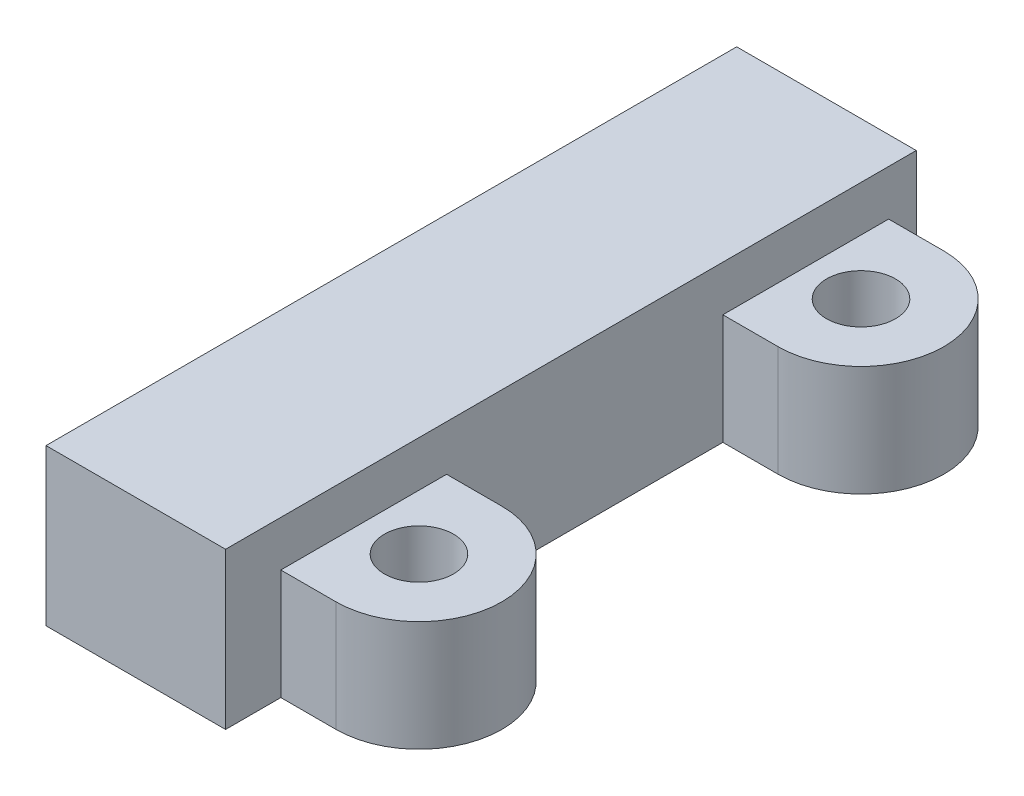
SolidWorks part; units mm, degrees
ref_plane "Alzado" through (0, 0, 0) normal (0, 0, 1) x (1, 0, 0)
ref_plane "Planta" through (0, 0, 0) normal (0, 1, 0) x (1, 0, 0)
ref_plane "Vista lateral" through (0, 0, 0) normal (1, 0, 0) x (0, 0, -1)
sketch "Croquis1" plane through (0, 0, 0) normal (0, 0, 1) x (1, 0, 0)
  line L0 (0, 0) -> (0, 11.3)
  line L1 (0, 11.3) -> (13, 11.3)
  line L2 (13, 11.3) -> (13, 6.3)
  line L3 (13, 6.3) -> (5, 6.3)
  line L4 (5, 6.3) -> (5, 0)
  line L5 (5, 0) -> (0, 0)
  dimension "D1" = 6.3
  dimension "D2" = 5
  dimension "D3" = 8
  dimension "D4" = 5
sketch "Croquis3" plane through (0, 0, 0) normal (0, 1, 0) x (1, 0, 0)
  line L0 (0, 0) -> (0, -37)
  dimension "D1" = 37
sweep "Barrer1" add profiles "Croquis1" path "Croquis3"
ref_plane "Plano1" through (80.5, 0, 0) normal (-1, 0, 0) x (0, 0, 1)
sketch "Croquis4" plane through (0, 0, 0) normal (-1, 0, 0) x (0, 0, 1)
  line L0 (0, 0) -> (37, 0) construction
  line L1 (37, 11.3) -> (50, 11.3)
  line L2 (37, 11.3) -> (37, 0)
  line L3 (37, 0) -> (50, 0)
  line L4 (50, 11.3) -> (50, 0)
  dimension "D1" = 13
extrude "Saliente-Extruir1" add sketch "Croquis4" against normal blind 161
mirror "Simetría5" about plane through (80.5, 0, 0) normal (-1, 0, 0) of "Barrer1"
sketch "Croquis5" plane through (0, 0, 0) normal (0, -1, 0) x (1, 0, 0)
  line L1 (5, 37) -> (156, 37)
  line L2 (5, 37) -> (5, 40.5)
  line L3 (5, 40.5) -> (156, 40.5)
  line L4 (156, 37) -> (156, 40.5)
  dimension "D1" = 3.5
  dimension "D2" = 151
extrude "Cortar-Extruir1" cut sketch "Croquis5" against normal blind 6.3
sketch "Croquis6" plane through (0, 0, 50) normal (0, 0, 1) x (1, 0, 0)
  line L0 (161, 11.3) -> (0, 11.3) construction
  line L1 (16, 11.3) -> (26, 11.3)
  line L2 (16, 11.3) -> (16, 14)
  line L4 (26, 11.3) -> (26, 14)
  line L5 (0, 0) -> (0, 11.3) construction
  arc A0 (26, 14) -> (16, 14) centre (21, 14) ccw
  dimension "D1" = 2.7
  dimension "D2" = 10
  dimension "D3" = 21
extrude "Saliente-Extruir2" [suppressed] add sketch "Croquis6" against normal blind 10
sketch "Croquis7" [suppressed] plane through (0, 0, 50) normal (0, 0, 1) x (1, 0, 0)
  circle A0 centre (21, 14) radius 3
  dimension "D1" = 6
extrude "Cortar-Extruir2" [suppressed] cut sketch "Croquis7" against normal through all
mirror "Simetría6" [suppressed] about plane through (80.5, 0, 0) normal (-1, 0, 0)
sketch "Croquis8" plane through (0, 0, 0) normal (0, -1, 0) x (1, 0, 0)
  line L0 (161, 0) -> (161, 50) construction
  line L1 (161, 46) -> (165, 46)
  line L2 (161, 46) -> (161, 34)
  line L3 (161, 34) -> (165, 34)
  line L5 (161, 50) -> (0, 50) construction
  arc A0 (165, 34) -> (165, 46) centre (165, 40) ccw
  dimension "D1" = 4
  dimension "D2" = 12
  dimension "D3" = 10
extrude "Saliente-Extruir3" add sketch "Croquis8" against normal blind 8
sketch "Croquis9" plane through (0, 0, 0) normal (0, -1, 0) x (1, 0, 0)
  circle A0 centre (165, 40) radius 2.5
  dimension "D1" = 5
extrude "Cortar-Extruir3" cut sketch "Croquis9" against normal through all
ref_plane "Plano2" through (0, 0, 24) normal (0, 0, -1) x (-1, 0, 0)
mirror "Simetría7" about plane through (0, 0, 24) normal (0, 0, -1) of "Saliente-Extruir3", "Cortar-Extruir3"
mirror "Simetría8" about plane through (80.5, 0, 0) normal (-1, 0, 0) of "Simetría7", "Saliente-Extruir3", "Cortar-Extruir3"
sketch "Croquis10" plane through (0, 11.3, 0) normal (0, 1, 0) x (1, 0, 0)
  line L0 (161, -50) -> (161, 0) construction
  line L1 (161, -50) -> (0, -50) construction
  circle A0 centre (121, -45.25) radius 2.5
  dimension "D3" = 5
  dimension "D1" = 40
  dimension "D2" = 4.75
extrude "Cortar-Extruir4" cut sketch "Croquis10" against normal through all
pattern_linear "MatrizL1" count 3 spacing 40.5 along (-1, 0, 0) of "Cortar-Extruir4"
ref_plane "Plano3" through (148, 0, 0) normal (-1, 0, 0) x (0, 0, 1)
sketch "Croquis11" plane through (148, 0, 0) normal (-1, 0, 0) x (0, 0, 1)
  line L1 (-6.1016, 16.4789) -> (55.8239, 16.4789)
  line L2 (-6.1016, 16.4789) -> (-6.1016, -4.9289)
  line L3 (-6.1016, -4.9289) -> (55.8239, -4.9289)
  line L4 (55.8239, 16.4789) -> (55.8239, -4.9289)
extrude "Cortar-Extruir5" cut sketch "Croquis11" along normal through all
